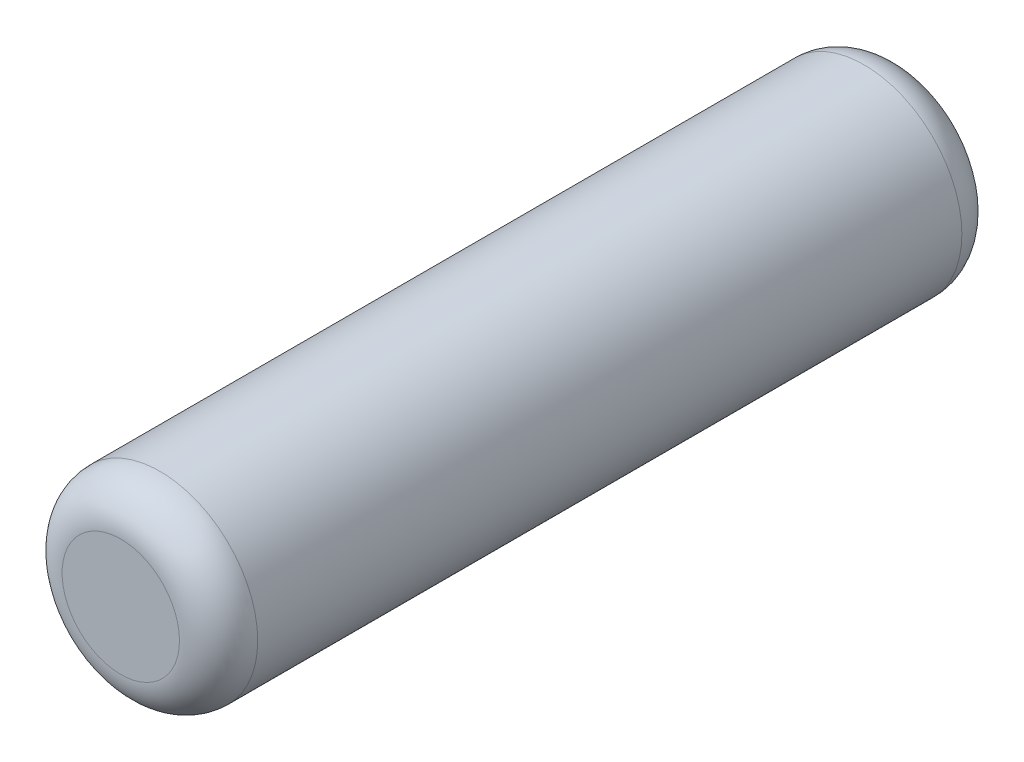
SolidWorks part; units mm, degrees
ref_plane "Alzado" through (0, 0, 0) normal (0, 0, 1) x (1, 0, 0)
ref_plane "Planta" through (0, 0, 0) normal (0, 1, 0) x (1, 0, 0)
ref_plane "Vista lateral" through (0, 0, 0) normal (1, 0, 0) x (0, 0, -1)
sketch "Croquis1" plane through (0, 0, 0) normal (0, 0, 1) x (1, 0, 0)
  circle A0 centre (0, 0) radius 2.5
  dimension "D1" = 5
extrude "Saliente-Extruir1" add sketch "Croquis1" along normal mid plane 20
fillet "Redondeo1" radius 1 2 edges at (2.5, 0, -10) (2.5, 0, 10)
